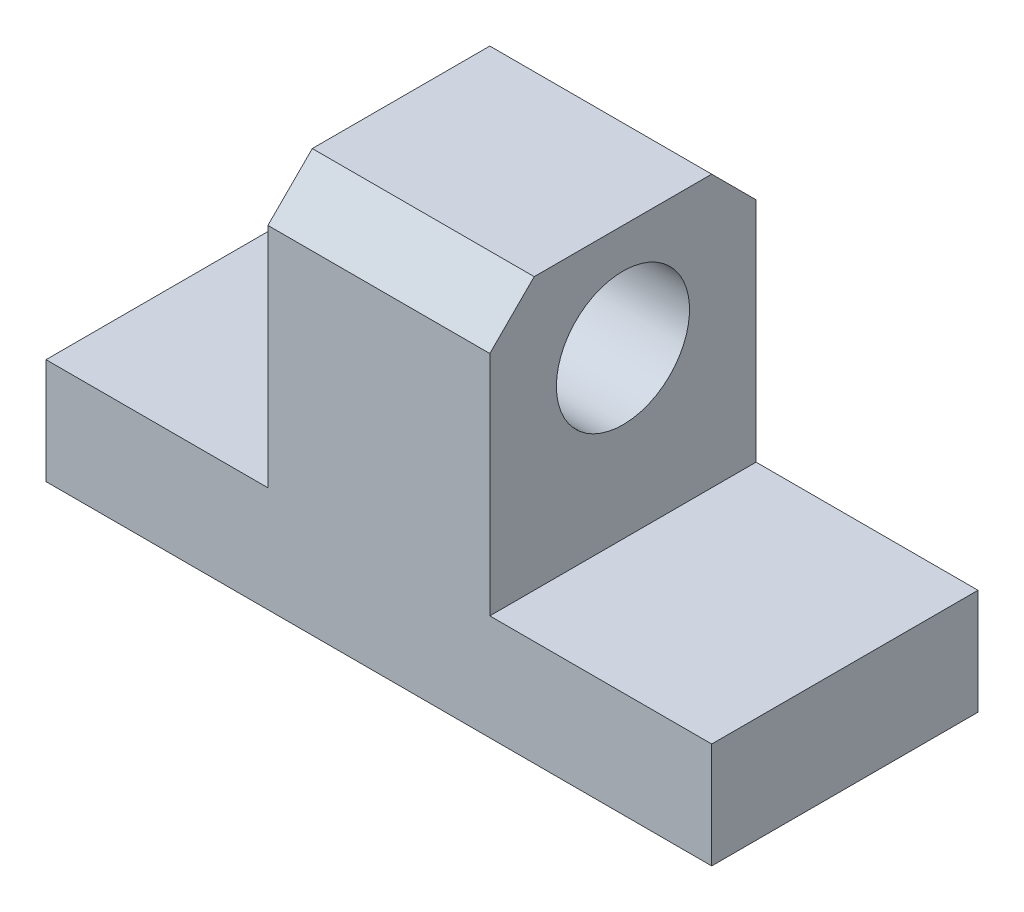
SolidWorks part; units mm, degrees
ref_plane "Спереди" through (0, 0, 0) normal (0, 0, 1) x (1, 0, 0)
ref_plane "Сверху" through (0, 0, 0) normal (0, 1, 0) x (1, 0, 0)
ref_plane "Справа" through (0, 0, 0) normal (1, 0, 0) x (0, 0, -1)
sketch "Эскиз2" plane through (0, 0, 0) normal (0, 0, 1) x (1, 0, 0)
  line L0 (0.8464, 0) -> (-29.1536, 0)
  line L1 (-14.1536, 0) -> (-14.1536, 18.4945) construction
  line L2 (-19.1536, 4.7601) -> (-19.1536, 17)
  line L3 (-24.1536, 24.0399) -> (-24.1536, 11.5951) construction
  line L4 (-29.1536, 4.7601) -> (-29.1536, 0)
  line L5 (-29.1536, 4.7601) -> (-19.1536, 4.7601)
  line L6 (-19.1536, 17) -> (-9.1536, 17)
  line L7 (0.8464, 4.7601) -> (-9.1536, 4.7601)
  line L8 (0.8464, 4.7601) -> (0.8464, 0)
  line L9 (-9.1536, 4.7601) -> (-9.1536, 17)
  point P11 (-14.1536, 17)
  dimension "D1" = 10
  dimension "D2" = 17
extrude "Вытянуть2" add sketch "Эскиз2" along normal blind 12
chamfer "Фаска1" distance 2 angle 45 2 edges at (-14.1536, 17, 0) (-14.1536, 17, 12)
sketch "Эскиз4" plane through (-19.1536, 0, 0) normal (-1, 0, 0) x (0, 0, 1)
  circle A0 centre (6, 12.217) radius 3
extrude "Вытянуть4" cut sketch "Эскиз4" against normal through all
